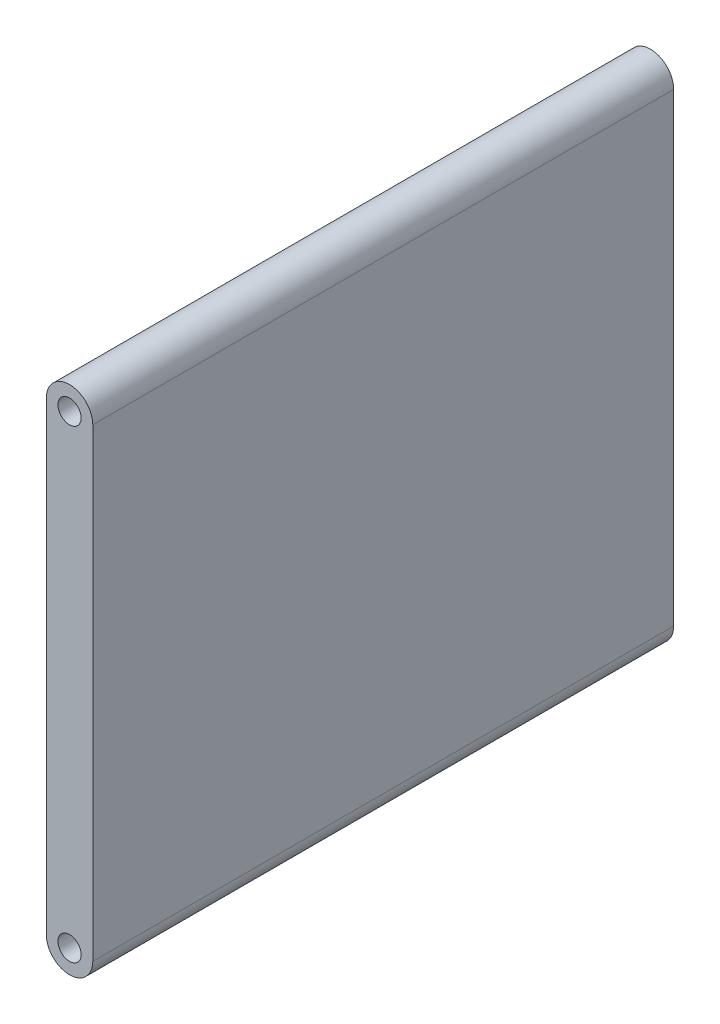
SolidWorks part; units mm, degrees
ref_plane "Alzado" through (0, 0, 0) normal (0, 0, 1) x (1, 0, 0)
ref_plane "Planta" through (0, 0, 0) normal (0, 1, 0) x (1, 0, 0)
ref_plane "Vista lateral" through (0, 0, 0) normal (1, 0, 0) x (0, 0, -1)
sketch "Croquis1" plane through (0, 0, 0) normal (0, 0, 1) x (1, 0, 0)
  line L0 (0, -28) -> (0, 28) construction
  line L1 (2.8, -28) -> (2.8, 28)
  line L2 (-2.8, -28) -> (-2.8, 28)
  circle A0 centre (0, 0) radius 32 construction
  arc A2 (2.8, -28) -> (-2.8, -28) centre (0, -28) cw
  arc A3 (2.8, 28) -> (-2.8, 28) centre (0, 28) ccw
  circle A4 centre (0, 28) radius 1.4
  circle A5 centre (0, -28) radius 1.4
  point P6 (0, 0)
  dimension "D1" = 64
  dimension "D5" = 2.8
  dimension "D2" = 56
  dimension "D3" = 2.8
  dimension "D4" = 2.8
extrude "Saliente-Extruir1" add sketch "Croquis1" along normal blind 70
